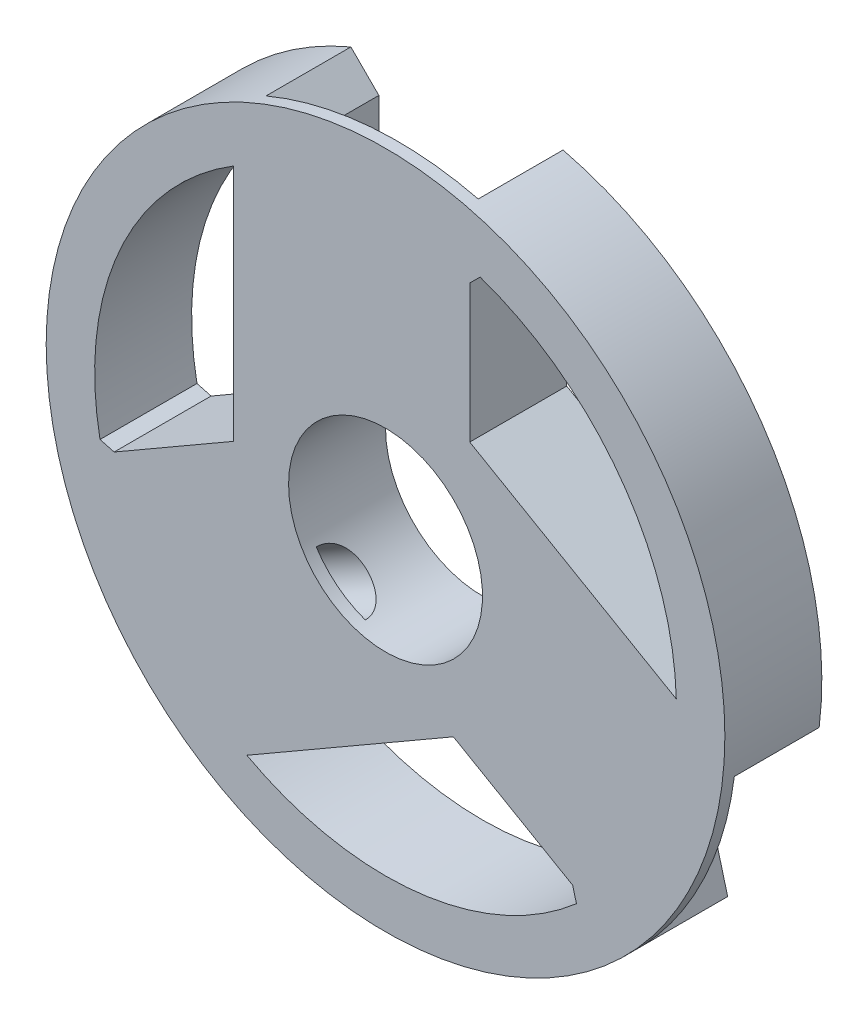
SolidWorks part; units mm, degrees
ref_plane "Front Plane" through (0, 0, 0) normal (0, 0, 1) x (1, 0, 0)
ref_plane "Top Plane" through (0, 0, 0) normal (0, 1, 0) x (1, 0, 0)
ref_plane "Right Plane" through (0, 0, 0) normal (1, 0, 0) x (0, 0, -1)
sketch "Sketch1" plane through (0, 0, 0) normal (0, 0, 1) x (1, 0, 0)
  circle A0 centre (0, 0) radius 250
  dimension "D1" = 500
extrude "Boss-Extrude1" add sketch "Sketch1" against normal blind 5
sketch "Sketch2" plane through (0, 0, -5) normal (0, 0, -1) x (-1, 0, 0)
  line L0 (0, 0) -> (0, 139.1218) construction
  line L1 (8.0171, -4.6287) -> (188.3301, -108.7325) construction
  line L2 (0, 0) -> (-167.4304, -96.666) construction
  line L3 (-73.3365, 7.0226) -> (-123.133, -21.7274)
  line L4 (-73.3365, 7.0226) -> (-44.5865, -42.7739)
  line L5 (-123.133, -21.7274) -> (-94.383, -71.5239)
  line L6 (-44.5865, -42.7739) -> (-94.383, -71.5239)
  line L7 (-73.3365, 7.0226) -> (-94.383, -71.5239) construction
  line L8 (-123.133, -21.7274) -> (-44.5865, -42.7739) construction
  line L9 (-14.75, 117.5) -> (-14.75, 60)
  line L10 (-14.75, 117.5) -> (42.75, 117.5)
  line L11 (-14.75, 60) -> (42.75, 60)
  line L12 (42.75, 117.5) -> (42.75, 60)
  line L13 (-14.75, 117.5) -> (42.75, 60) construction
  line L14 (-14.75, 60) -> (42.75, 117.5) construction
  line L15 (80.383, -95.7726) -> (30.5865, -67.0226)
  line L16 (80.383, -95.7726) -> (109.133, -45.9761)
  line L17 (30.5865, -67.0226) -> (59.3365, -17.2261)
  line L18 (109.133, -45.9761) -> (59.3365, -17.2261)
  line L19 (80.383, -95.7726) -> (59.3365, -17.2261) construction
  line L20 (30.5865, -67.0226) -> (109.133, -45.9761) construction
  circle A1 centre (0, 0) radius 250 construction
  circle A2 centre (0, 0) radius 250
  point P6 (14, 88.75)
  point P9 (59.5392, -34.375)
  point P10 (-59.5392, -34.375)
  point P11 (0, 68.75)
  point P13 (-83.8598, -32.2506)
  point P15 (69.8598, -56.4994)
  dimension "D1" = 57.5
  dimension "D2" = 57.5
  dimension "D3" = 14
  dimension "D4" = 60
  dimension "D5" = 45
  dimension "D6" = 57.5
  dimension "D7" = 57.5
  dimension "D8" = 14
  dimension "D9" = 60
  dimension "D10" = 45
  dimension "D11" = 57.5
  dimension "D12" = 57.5
  dimension "D13" = 14
  dimension "D14" = 60
extrude "Boss-Extrude2" add sketch "Sketch2" along normal blind 35
sketch "Sketch3" plane through (0, 0, -40) normal (0, 0, -1) x (-1, 0, 0)
  circle A0 centre (0, 0) radius 140
  circle A1 centre (0, 0) radius 250 construction
  circle A2 centre (0, 0) radius 250
  dimension "D1" = 280
extrude "Cut-Extrude1" cut sketch "Sketch3" against normal through all
sketch "Sketch4" plane through (0, 0, -40) normal (0, 0, -1) x (-1, 0, 0)
  line L0 (42.75, 117.5) -> (54.2935, 129.0435)
  line L1 (-14.75, 117.5) -> (-33.2454, 135.9954)
  line L2 (-123.133, -21.7274) -> (-138.9017, -17.5022)
  line L3 (-94.383, -71.5239) -> (-101.1528, -96.789)
  line L4 (80.383, -95.7726) -> (84.6082, -111.5413)
  line L5 (109.133, -45.9761) -> (134.3981, -39.2063)
  line L6 (42.75, 60) -> (42.75, 117.5) construction
  line L7 (-14.75, 117.5) -> (-14.75, 60) construction
  line L8 (-73.3365, 7.0226) -> (-123.133, -21.7274) construction
  line L9 (-94.383, -71.5239) -> (-44.5865, -42.7739) construction
  line L10 (30.5865, -67.0226) -> (80.383, -95.7726) construction
  line L11 (109.133, -45.9761) -> (59.3365, -17.2261) construction
  line L12 (42.75, 117.5) -> (-14.75, 117.5) construction
  line L13 (80.383, -95.7726) -> (109.133, -45.9761) construction
  line L14 (-123.133, -21.7274) -> (-94.383, -71.5239) construction
  line L15 (42.75, 117.5) -> (-14.75, 117.5)
  line L16 (80.383, -95.7726) -> (109.133, -45.9761)
  line L17 (-123.133, -21.7274) -> (-94.383, -71.5239)
  circle A0 centre (0, 0) radius 140 construction
  arc A1 (-138.9017, -17.5022) -> (-101.1528, -96.789) centre (0, 0) ccw
  arc A2 (54.2935, 129.0435) -> (-33.2454, 135.9954) centre (0, 0) ccw
  arc A3 (84.6082, -111.5413) -> (134.3981, -39.2063) centre (0, 0) ccw
  dimension "D1" = 135
  dimension "D2" = 135
  dimension "D3" = 135
  dimension "D4" = 135
  dimension "D5" = 135
  dimension "D6" = 135
extrude "Cut-Extrude2" cut sketch "Sketch4" against normal up to surface (35 mm away) up to face at (83.8598, -32.2506, -5)
sketch "Sketch5" plane through (0, 0, -40) normal (0, 0, -1) x (-1, 0, 0)
  circle A0 centre (0, 0) radius 40
  dimension "D1" = 80
extrude "Cut-Extrude3" cut sketch "Sketch5" against normal through all
sketch "Sketch7" plane through (-51.9615, -30, 0) normal (-0.866, -0.5, 0) x (0, 0, 1)
  line L0 (-5, 14.75) -> (-5, -42.75) construction
  line L1 (-5, -26) -> (-5, -2)
  arc A0 (-5, -26) -> (-5, -2) centre (-5, -14) cw
  dimension "D1" = 12
extrude "Cut-Extrude4" cut sketch "Sketch7" against normal up to surface (29.6026 mm away)
sketch "Sketch8" plane through (0, 60, 0) normal (0, 1, 0) x (1, 0, 0)
  line L0 (14.75, 5) -> (-42.75, 5) construction
  line L1 (-26, 5) -> (-2, 5)
  arc A0 (-26, 5) -> (-2, 5) centre (-14, 5) cw
  dimension "D1" = 12
extrude "Cut-Extrude5" cut sketch "Sketch8" against normal up to surface (29.6026 mm away)
sketch "Sketch9" plane through (51.9615, -30, 0) normal (0.866, -0.5, 0) x (0, 0, -1)
  line L0 (5, -14.75) -> (5, 42.75) construction
  line L1 (5, 26) -> (5, 2)
  arc A0 (5, 26) -> (5, 2) centre (5, 14) cw
  dimension "D1" = 12
extrude "Cut-Extrude6" cut sketch "Sketch9" against normal up to surface (29.6026 mm away)
sketch "Sketch10" plane through (0, 0, -40) normal (0, 0, -1) x (-1, 0, 0)
  line L15 (62.75, 40) -> (62.75, 3.8971)
  line L16 (3.266, -74.3431) -> (-28, -56.2917)
  line L17 (-66.016, 34.3431) -> (-34.75, 52.3945)
  line L30 (57.2073, -105.4861) -> (3.266, -74.3431)
  line L31 (3.266, -74.3431) -> (52.016, 10.0944)
  line L32 (52.016, 10.0944) -> (111.9586, -24.5135)
  line L33 (111.9586, -24.5135) -> (117.7845, -22.9524)
  line L34 (62.75, 102.2861) -> (62.75, 40)
  line L35 (62.75, 40) -> (-34.75, 40)
  line L36 (-34.75, 40) -> (-34.75, 109.2157)
  line L37 (-34.75, 109.2157) -> (-39.0148, 113.4806)
  line L38 (-119.9573, 3.2001) -> (-66.016, 34.3431)
  line L39 (-66.016, 34.3431) -> (-17.266, -50.0944)
  line L40 (-17.266, -50.0944) -> (-77.2086, -84.7022)
  line L41 (-77.2086, -84.7022) -> (-78.7696, -90.5281)
  line L42 (57.2073, -105.4861) -> (3.266, -74.3431)
  line L44 (62.75, 3.8971) -> (111.9586, -24.5135)
  line L45 (111.9586, -24.5135) -> (117.7845, -22.9524)
  line L46 (62.75, 102.2861) -> (62.75, 40)
  line L48 (-34.75, 52.3945) -> (-34.75, 109.2157)
  line L49 (-34.75, 109.2157) -> (-39.0148, 113.4806)
  line L50 (-119.9573, 3.2001) -> (-66.016, 34.3431)
  line L52 (-28, -56.2917) -> (-77.2086, -84.7022)
  line L53 (-77.2086, -84.7022) -> (-78.7696, -90.5281)
  arc A6 (117.7845, -22.9524) -> (62.75, 102.2861) centre (0, 0) ccw
  arc A7 (-39.0148, 113.4806) -> (-119.9573, 3.2001) centre (0, 0) ccw
  arc A8 (-78.7696, -90.5281) -> (57.2073, -105.4861) centre (0, 0) ccw
  arc A9 (117.7845, -22.9524) -> (62.75, 102.2861) centre (0, 0) ccw
  arc A10 (-39.0148, 113.4806) -> (-119.9573, 3.2001) centre (0, 0) ccw
  arc A11 (-78.7696, -90.5281) -> (57.2073, -105.4861) centre (0, 0) ccw
  dimension "D1" = 20
extrude "Cut-Extrude7" cut sketch "Sketch10" against normal through all
